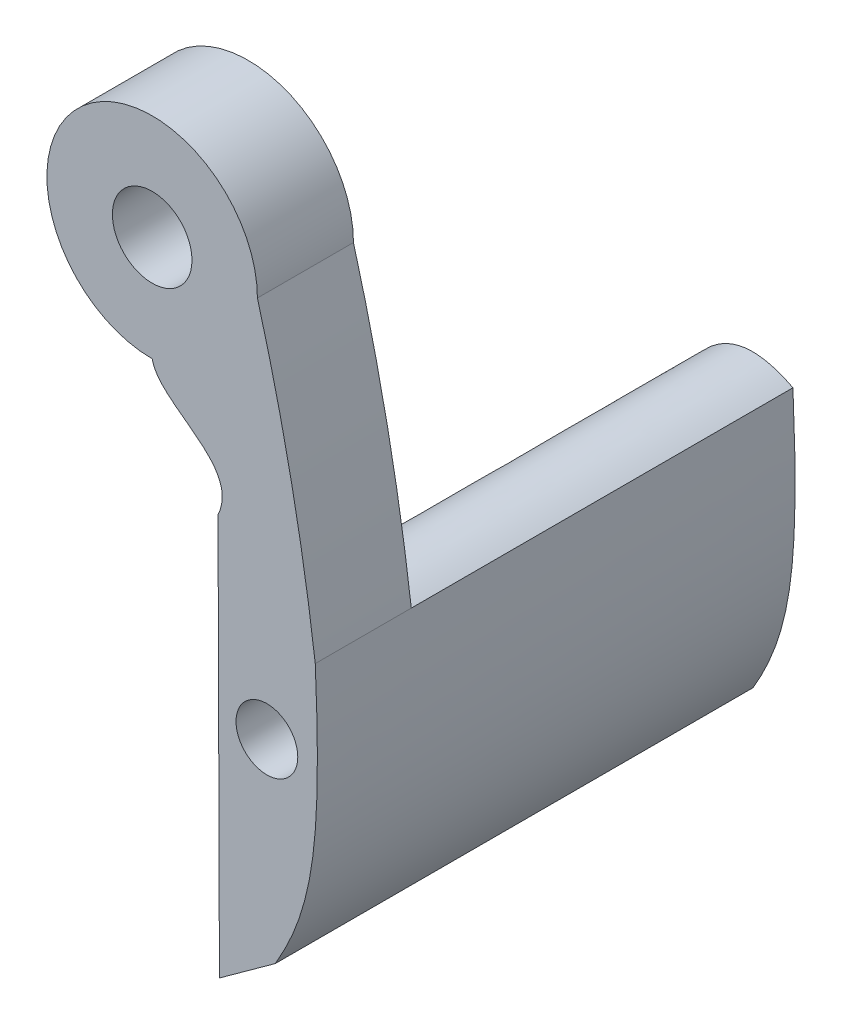
SolidWorks part; units mm, degrees
ref_plane "Front Plane" through (0, 0, 0) normal (0, 0, 1) x (1, 0, 0)
ref_plane "Top Plane" through (0, 0, 0) normal (0, 1, 0) x (1, 0, 0)
ref_plane "Right Plane" through (0, 0, 0) normal (1, 0, 0) x (0, 0, -1)
sketch "Sketch1" plane through (0, 0, 0) normal (0, 0, 1) x (1, 0, 0)
  line L47 (23.6842, -79.8541) -> (27.7517, -76.9116)
  line L48 (23.6087, -58.0448) -> (23.6842, -79.8541)
  line L93 (23.5831, -50.6621) -> (23.6087, -58.0448)
  arc A44 (26.4535, -35.5548) -> (18.783, -43.2252) centre (18.783, -35.5548) ccw
  circle A45 centre (18.783, -35.5548) radius 2.9
  spline S0 degree 2 poles (30.6681, -56.5171) (29.3204, -45.8837) (26.4535, -35.5548) knots 0 0 0 1 1 1
  spline S3 degree 3 poles (27.7517, -76.9116) (30.6656, -71.9964) (31.1322, -67.2565) (30.6681, -56.5171) knots 0.222416 0.222416 0.222416 0.222416 0.766683 0.766683 0.766683 0.766683
  spline S5 degree 3 poles (18.783, -43.2252) (19.3228, -45.8172) (25.2941, -46.9406) (23.5831, -50.6621) knots 0 0 0 0 1 1 1 1
extrude "Boss-Extrude1" add sketch "Sketch1" against normal blind 7
sketch "Sketch2" plane through (0, 0, -7) normal (0, 0, -1) x (-1, 0, 0)
  line L4 (-27.7517, -76.9116) -> (-23.6842, -79.8541)
  line L5 (-23.6842, -79.8541) -> (-23.6087, -58.0448)
  parabola Q2 (-23.6087, -58.0448) -> (-30.6681, -56.5171) focus (-27.211, -57.9236) apex (-26.7179, -55.8255)
  spline S2 degree 3 poles (-30.6681, -56.5171) (-31.1322, -67.2565) (-30.6656, -71.9964) (-27.7517, -76.9116) knots 0.222416 0.222416 0.222416 0.222416 0.766683 0.766683 0.766683 0.766683
extrude "Boss-Extrude2" add sketch "Sketch2" along normal blind 27.8124
sketch "Sketch3" plane through (0, 0, 0) normal (0, 0, 1) x (1, 0, 0)
  circle A0 centre (27.1437, -63.0557) radius 2.25
  dimension "D1" = 4.5
extrude "Cut-Extrude1" cut sketch "Sketch3" against normal through all
